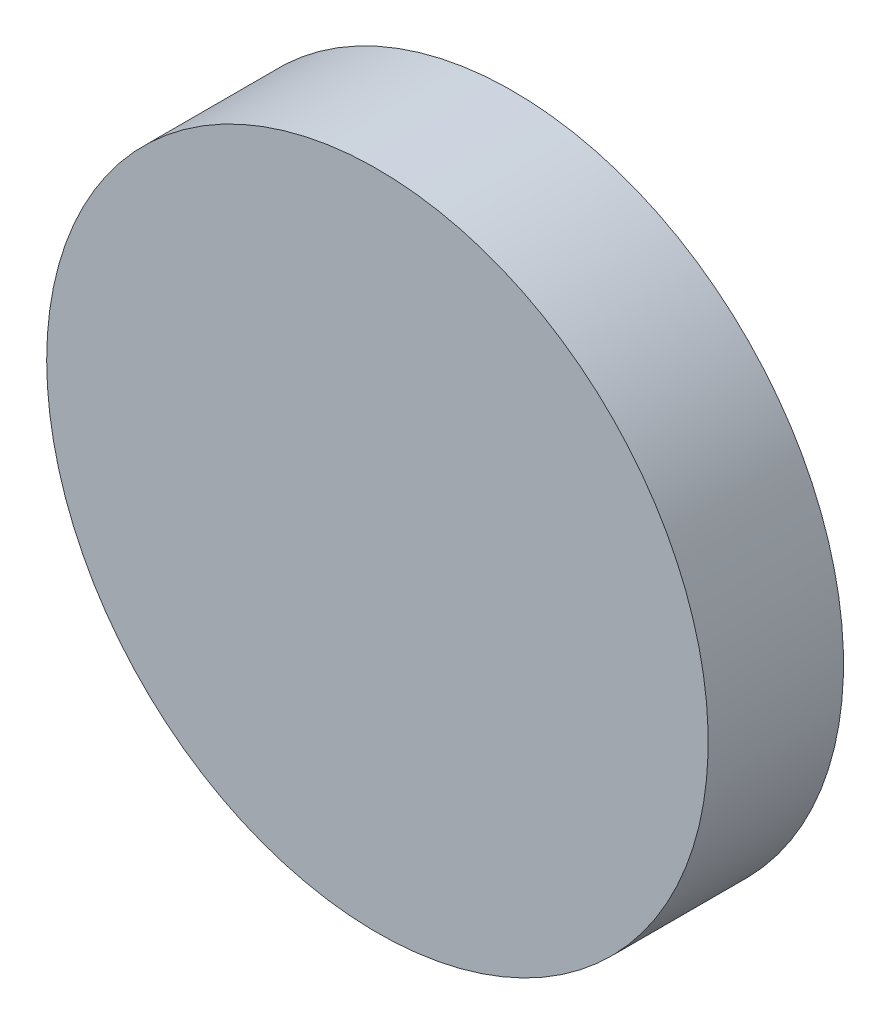
SolidWorks part; units mm, degrees
ref_plane "Front Plane" through (0, 0, 0) normal (0, 0, 1) x (1, 0, 0)
ref_plane "Top Plane" through (0, 0, 0) normal (0, 1, 0) x (1, 0, 0)
ref_plane "Right Plane" through (0, 0, 0) normal (1, 0, 0) x (0, 0, -1)
sketch "Sketch1" plane through (0, 0, 0) normal (0, 0, 1) x (1, 0, 0)
  circle A1 centre (0, 0) radius 110
extrude "Boss-Extrude2" add sketch "Sketch1" along normal blind 45
sketch "Sketch3" plane through (0, 0, 0) normal (0, 0, 1) x (1, 0, 0)
  circle A0 centre (0, 0) radius 91.6
extrude "Cut-Extrude1" cut sketch "Sketch3" along normal offset from surface (35 mm away) 10 up to face at (110, 0, 45)
